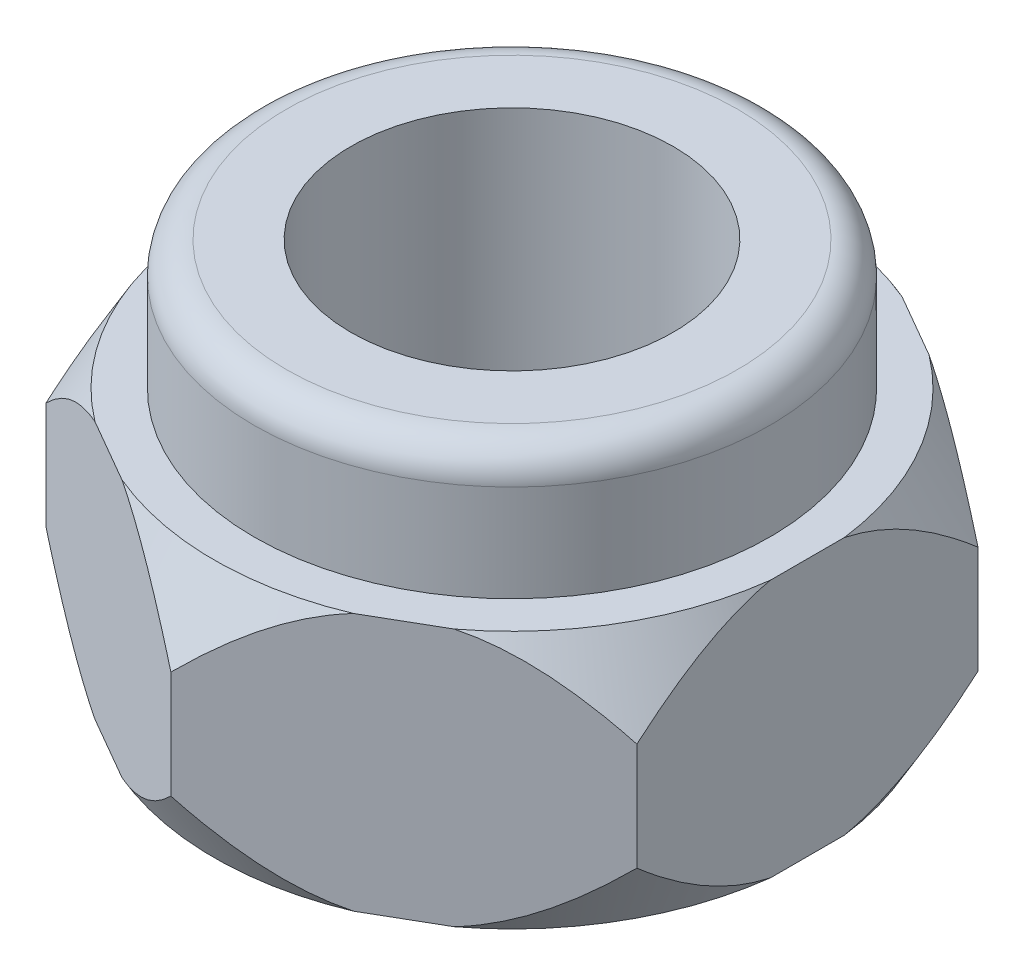
SolidWorks part; units mm, degrees
ref_plane "前视基准面" through (0, 0, 0) normal (0, 0, 1) x (1, 0, 0)
ref_plane "上视基准面" through (0, 0, 0) normal (0, 1, 0) x (1, 0, 0)
ref_plane "右视基准面" through (0, 0, 0) normal (1, 0, 0) x (0, 0, -1)
sketch "草图1" plane through (0, 0, 0) normal (0, 1, 0) x (1, 0, 0)
  line L1 (0, 3.1754) -> (-2.75, 1.5877)
  line L2 (-2.75, 1.5877) -> (-2.75, -1.5877)
  line L3 (-2.75, -1.5877) -> (0, -3.1754)
  line L4 (0, -3.1754) -> (2.75, -1.5877)
  line L5 (2.75, -1.5877) -> (2.75, 1.5877)
  line L6 (2.75, 1.5877) -> (0, 3.1754)
  circle A0 centre (0, 0) radius 2.75 construction
  circle A1 centre (0, 0) radius 1.5
  dimension "D1" = 3
  dimension "D2" = 5.5
extrude "凸台-拉伸1" add sketch "草图1" along normal blind 2.4
cosmetic thread "装饰螺纹线1" parameters "D2"=9
sketch "草图3" plane through (0, 0, 0) normal (1, 0, 0) x (0, 0, -1)
  line L0 (0, 2.4) -> (0, 7.2) construction
  line L1 (-1.5877, 2.4) -> (1.5877, 2.4) construction
  line L2 (0, 7.2) -> (3.4641, 1.2) construction
  line L3 (0.3843, 7.2) -> (4.0835, 7.2)
  line L4 (4.0835, 7.2) -> (4.0835, -4.8)
  line L5 (-1.5877, 1.2) -> (6.6733, 1.2) construction
  line L6 (-1.5877, 2.4) -> (-1.5877, 0) construction
  line L7 (0.3843, 6.5344) -> (0.3843, 7.2)
  line L8 (0.2977, -4.8) -> (4.0835, -4.8)
  line L9 (0, -4.8) -> (3.4641, 1.2) construction
  line L10 (0.2977, -4.2844) -> (0.2977, -4.8)
  line L11 (0.3843, 6.5344) -> (3.4641, 1.2)
  line L12 (3.4641, 1.2) -> (0.2977, -4.2844)
  dimension "D1" = 4.8
  dimension "D2" = 30
revolve "切除-旋转7" cut sketch "草图3" angle 360 about axis through (0, 2.4, 0) along (0, -1, 0)
sketch "草图4" plane through (0, 2.4, 0) normal (0, 1, 0) x (1, 0, 0)
  circle A0 centre (0, 0) radius 1.5
  circle A1 centre (0, 0) radius 2.4
  dimension "D1" = 4.8
extrude "凸台-拉伸3" add sketch "草图4" along normal blind 1.2
fillet "圆角5" radius 0.3 1 edges at (0, 3.6, 2.4)
scale "缩放比例1" scale about centroid uniform scaling yes scale factor 2
